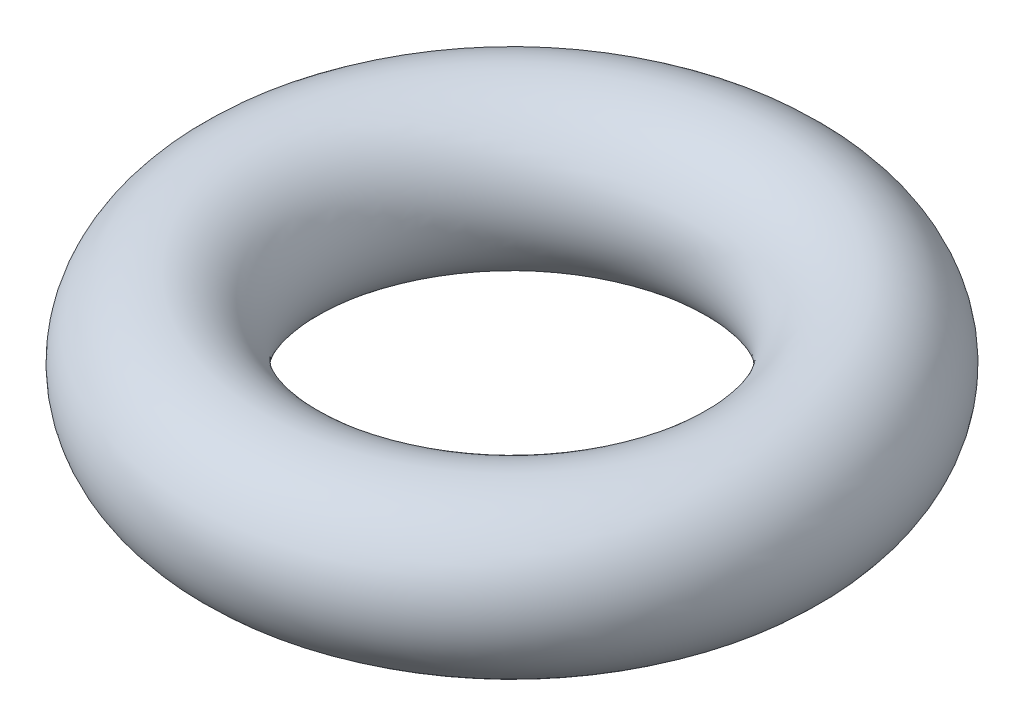
SolidWorks part; units mm, degrees
ref_plane "Front Plane" through (0, 0, 0) normal (0, 0, 1) x (1, 0, 0)
ref_plane "Top Plane" through (0, 0, 0) normal (0, 1, 0) x (1, 0, 0)
ref_plane "Right Plane" through (0, 0, 0) normal (1, 0, 0) x (0, 0, -1)
other "Configuration Table"
sketch "Sketch1" plane through (0, 0, 0) normal (0, 1, 0) x (1, 0, 0)
  circle A0 centre (0, 0) radius 3
sweep "Sweep1" add path "Sketch1" circular profile diameter 1.9 parameters "D3"=1.9
sketch "Sketch6" plane through (0, 0, 0) normal (0, 1, 0) x (1, 0, 0)
  circle A0 centre (0, 0) radius 1.6
